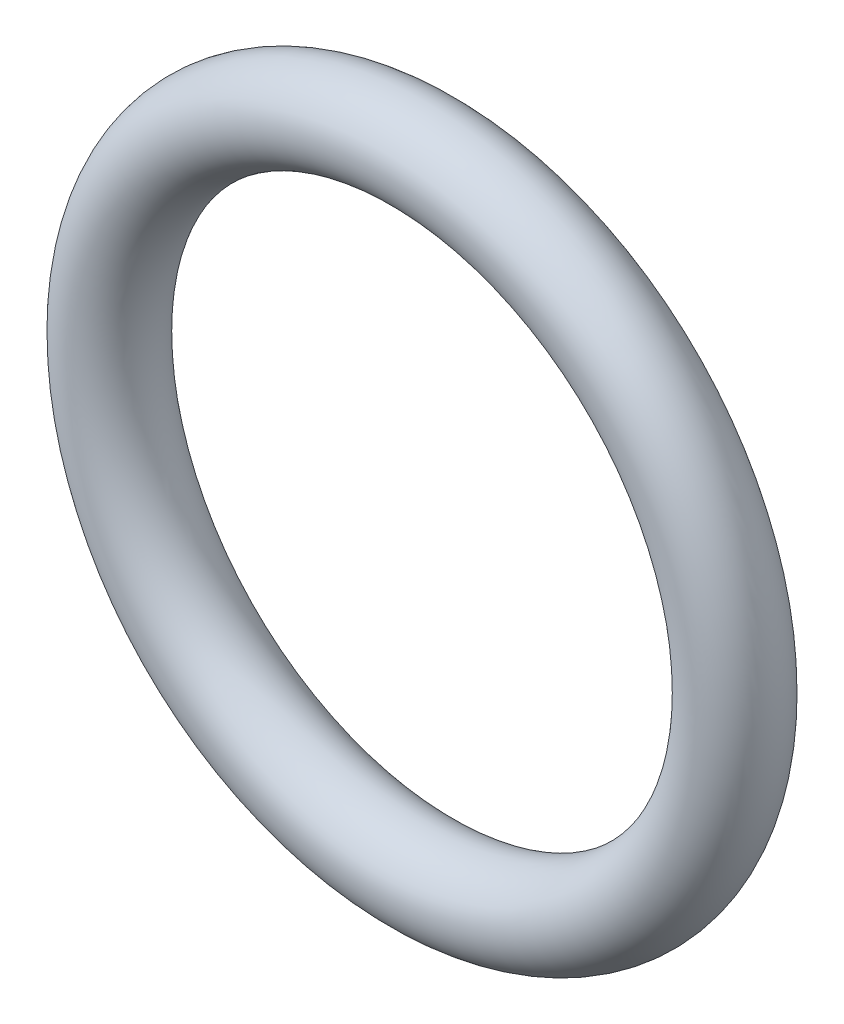
SolidWorks part; units mm, degrees
ref_plane "Front" through (0, 0, 0) normal (0, 0, 1) x (1, 0, 0)
ref_plane "Top" through (0, 0, 0) normal (0, 1, 0) x (1, 0, 0)
ref_plane "Right" through (0, 0, 0) normal (1, 0, 0) x (0, 0, -1)
sketch "Sketch1" plane through (0, 0, 0) normal (1, 0, 0) x (0, -1, 0)
  line L0 (0, -0.889) -> (0, 0.889) construction
  line L2 (-7.907, 0) -> (7.907, 0) construction
  line L3 (-5.4102, 0) -> (5.4102, 0) construction
  circle A0 centre (6.2992, 0) radius 0.889
  point P9 (5.4102, 0)
  point P10 (7.1882, 0)
  point P13 (6.2992, 0.889)
  point P14 (6.2992, -0.889)
  dimension "Width" = 1.778
  dimension "ID" = 10.8204
revolve "Revolve1" add sketch "Sketch1" angle 360 about L0
